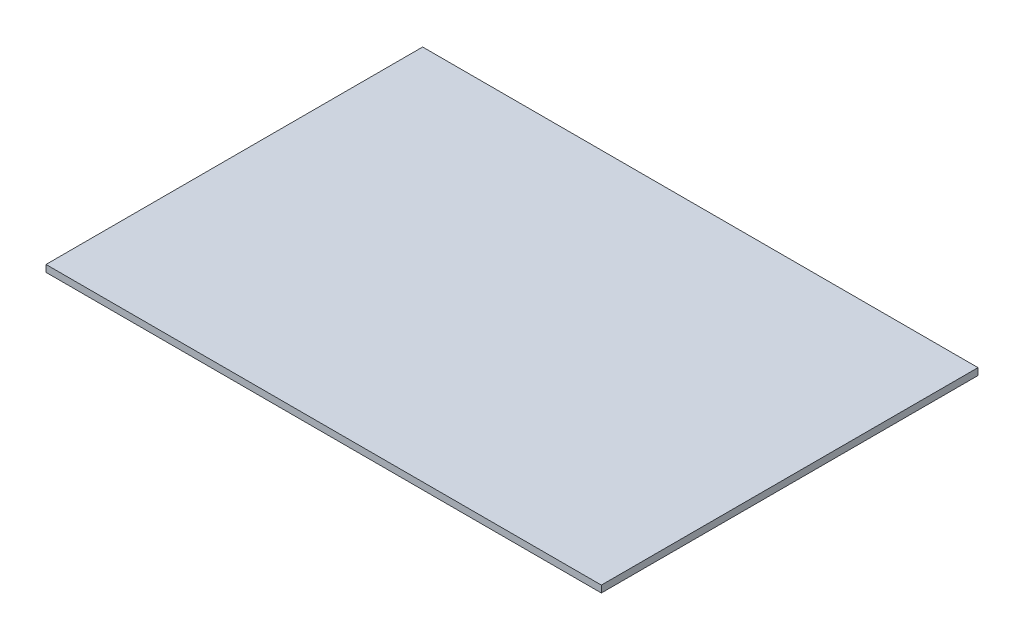
SolidWorks part; units mm, degrees
ref_plane "Front Plane" through (0, 0, 0) normal (0, 0, 1) x (1, 0, 0)
ref_plane "Top Plane" through (0, 0, 0) normal (0, 1, 0) x (1, 0, 0)
ref_plane "Right Plane" through (0, 0, 0) normal (1, 0, 0) x (0, 0, -1)
sketch "Sketch1" plane through (0, 0, 0) normal (0, 1, 0) x (1, 0, 0)
  line L1 (-102.5808, -69.5721) -> (102.5808, -69.5721)
  line L2 (-102.5808, -69.5721) -> (-102.5808, 69.5721)
  line L3 (-102.5808, 69.5721) -> (102.5808, 69.5721)
  line L4 (102.5808, -69.5721) -> (102.5808, 69.5721)
  line L5 (-102.5808, -69.5721) -> (102.5808, 69.5721) construction
  line L6 (-102.5808, 69.5721) -> (102.5808, -69.5721) construction
  point P0 (0, 0)
extrude "Boss-Extrude1" add sketch "Sketch1" along normal blind 2.54
sketch "Sketch2" plane through (0, 2.54, 0) normal (0, 1, 0) x (1, 0, 0)
  point P0 (-20.1441, -17.1481)
  line B0 (-17.7338, -0.0784) -> (-37.2137, -19.5584)
  line B1 (-37.0999, -27.967) -> (-28.9012, -33.7078)
  line B2 (-21.3869, -33.0503) -> (-4.2418, -15.9052)
  line B3 (-3.5844, -8.391) -> (-9.3252, -0.1923)
  arc B4 (-9.3252, -0.1923) -> (-17.7338, -0.0784) centre (-13.5849, -4.2273) ccw
  arc B5 (-37.2137, -19.5584) -> (-37.0999, -27.967) centre (-33.0648, -23.7073) ccw
  arc B6 (-28.9012, -33.7078) -> (-21.3869, -33.0503) centre (-25.5358, -28.9015) ccw
  arc B7 (-4.2418, -15.9052) -> (-3.5844, -8.391) centre (-8.3907, -11.7564) ccw
  circle B8 centre (-65.0123, -34.7842) radius 4.2469
  circle B9 centre (-0.7036, 2.2924) radius 4.2469
  circle B10 centre (-20.1441, -17.1481) radius 7.8542
sketch_block_instance "Block-9PinDsubFemale-1"
sketch_block "Block-9PinDsubFemale" parameters "D4"=4.572, "D1"=10.16, "D2"=16.51, "D3"=20.32, "D5"=24.9428
sketch_block_instance "Block-9PinDsubFemale-2"
sketch_block_instance "VGA-Cutout-2"
sketch_block "VGA-Cutout"
sketch_block_instance "Block1-1"
sketch_block "Block1"
